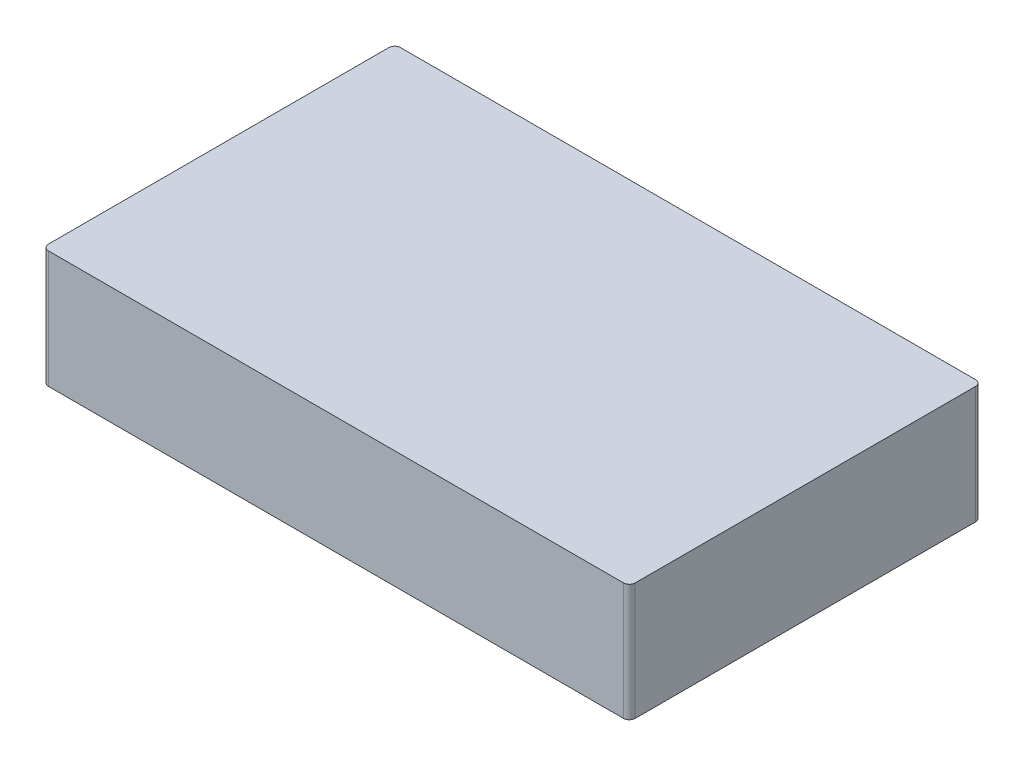
SolidWorks part; units mm, degrees
ref_plane "前视基准面" through (0, 0, 0) normal (0, 0, 1) x (1, 0, 0)
ref_plane "上视基准面" through (0, 0, 0) normal (0, 1, 0) x (1, 0, 0)
ref_plane "右视基准面" through (0, 0, 0) normal (1, 0, 0) x (0, 0, -1)
sketch "草图1" plane through (0, 0, 0) normal (0, 1, 0) x (1, 0, 0)
  line L1 (-49, 30) -> (49, 30)
  line L2 (-50, 29) -> (-50, -29)
  line L3 (-49, -30) -> (49, -30)
  line L4 (50, 29) -> (50, -29)
  line L5 (-50, 30) -> (50, -30) construction
  line L6 (-50, -30) -> (50, 30) construction
  arc A0 (50, 29) -> (49, 30) centre (49, 29) ccw
  arc A1 (-49, 30) -> (-50, 29) centre (-49, 29) ccw
  arc A2 (-50, -29) -> (-49, -30) centre (-49, -29) ccw
  arc A3 (49, -30) -> (50, -29) centre (49, -29) ccw
  point P0 (0, 0)
  dimension "D3" = 1
  dimension "D1" = 100
  dimension "D2" = 60
extrude "凸台-拉伸1" add sketch "草图1" along normal blind 20
